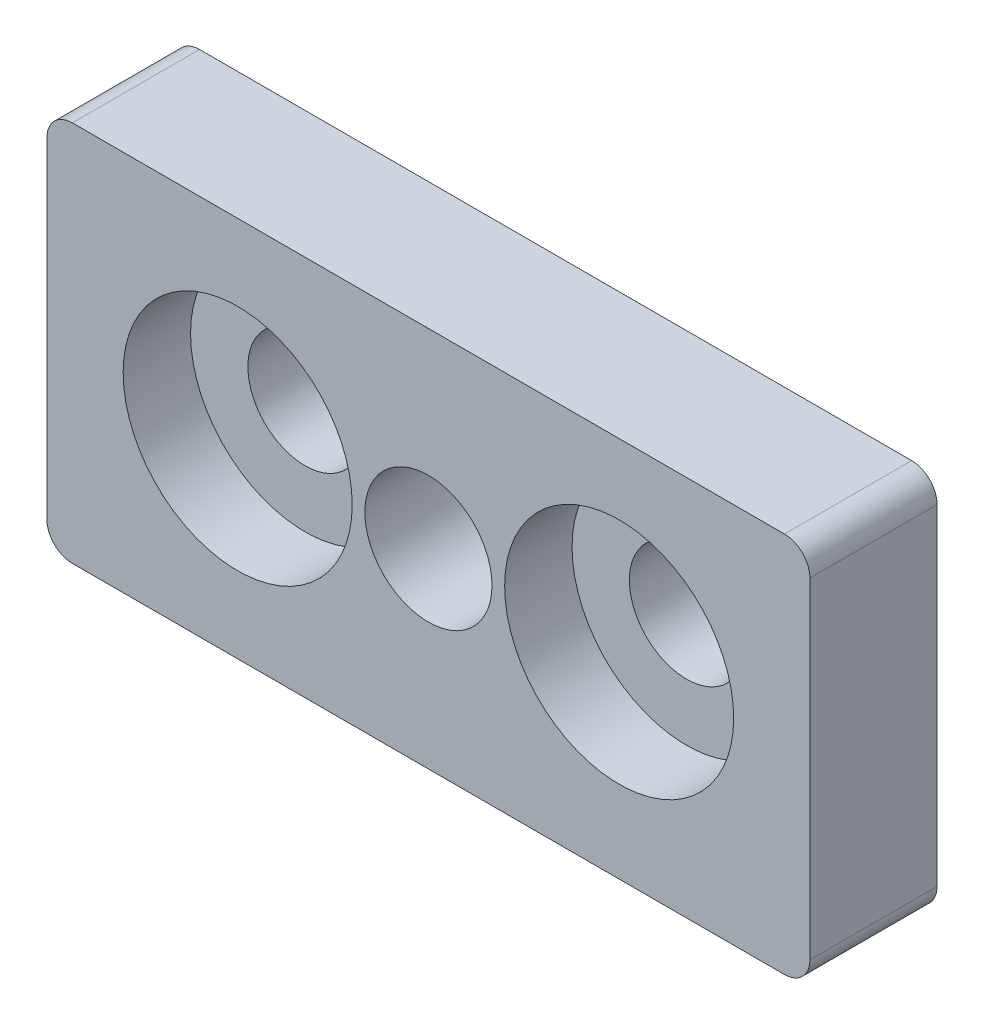
SolidWorks part; units mm, degrees
ref_plane "Front Plane" through (0, 0, 0) normal (0, 0, 1) x (1, 0, 0)
ref_plane "Top Plane" through (0, 0, 0) normal (0, 1, 0) x (1, 0, 0)
ref_plane "Right Plane" through (0, 0, 0) normal (1, 0, 0) x (0, 0, -1)
ref_plane "Plane1" through (0, 0, 10) normal (0, 0, 1) x (1, 0, 0)
sketch "Sketch1" plane through (0, 0, 10) normal (0, 0, 1) x (1, 0, 0)
  line L0 (30, 15) -> (-30, 15)
  line L1 (-30, 15) -> (-30, -15)
  line L2 (-30, -15) -> (30, -15)
  line L3 (30, -15) -> (30, 15)
extrude "Boss-Extrude1" add sketch "Sketch1" against normal blind 10
hole_wizard "Ø10.0 (10) Diameter Hole1" positions "Sketch3" profile "Sketch2" hole size "Ø10.0" standard "ANSI Metric"
sketch "Sketch3" plane through (0, 0, 10) normal (0, 0, 1) x (1, 0, 0)
  point P0 (0, 0)
sketch "Sketch2" plane through (0, 0, 10) normal (1, 0, 0) x (0, -1, 0)
  line L0 (0, 0) -> (0, 10)
  line L1 (0, 10) -> (5, 10)
  line L2 (5, 10) -> (5, 0)
  line L5 (5, 0) -> (0, 0)
  line L11 (0, -6.35) -> (0, 107.95) construction
  dimension "Thru Hole Dia." = 10
  dimension "Thru Hole Depth" = 10
hole_wizard "CBORE for M8 Hex Head Bolt1" positions "Sketch5" profile "Sketch4" counterbore size "M8" standard "ANSI Metric"
sketch "Sketch5" plane through (0, 0, 10) normal (0, 0, 1) x (1, 0, 0)
  point P0 (-15, 0)
  point P1 (15, 0.4628)
sketch "Sketch4" plane through (-15, 0, 10) normal (1, 0, 0) x (0, -1, 0)
  line L0 (0, 0) -> (0, 10)
  line L1 (0, 10) -> (4.5, 10)
  line L3 (4.5, 10) -> (4.5, 5.3)
  line L4 (4.5, 5.3) -> (9.0055, 5.3)
  line L5 (9.0055, 5.3) -> (9.0055, 0)
  line L7 (9.0055, 0) -> (0, 0)
  line L11 (0, -6.35) -> (0, 107.95) construction
  dimension "Thru Hole Dia." = 9
  dimension "Thru Hole Depth" = 10
  dimension "C'Bore Dia." = 18.011
  dimension "C'Bore Depth" = 5.3
fillet "Fillet1" radius 2 4 edges at (-30, -15, 5) (-30, 15, 5) (30, -15, 5) (30, 15, 5)
